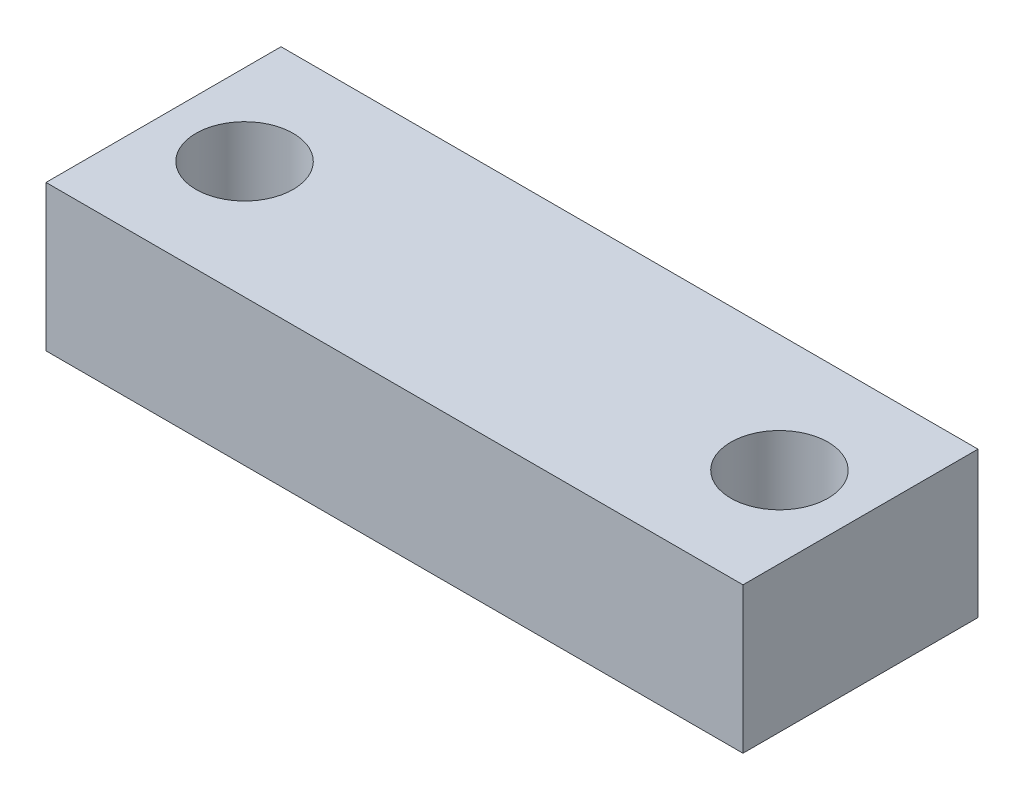
SolidWorks part; units mm, degrees
ref_plane "Front Plane" through (0, 0, 0) normal (0, 0, 1) x (1, 0, 0)
ref_plane "Top Plane" through (0, 0, 0) normal (0, 1, 0) x (1, 0, 0)
ref_plane "Right Plane" through (0, 0, 0) normal (1, 0, 0) x (0, 0, -1)
sketch "Sketch1" plane through (0, 0, 0) normal (0, 1, 0) x (1, 0, 0)
  line L1 (-21.5, 7.25) -> (21.5, 7.25)
  line L2 (-21.5, 7.25) -> (-21.5, -7.25)
  line L3 (-21.5, -7.25) -> (21.5, -7.25)
  line L4 (21.5, 7.25) -> (21.5, -7.25)
  line L5 (-21.5, 7.25) -> (21.5, -7.25) construction
  line L6 (-21.5, -7.25) -> (21.5, 7.25) construction
  point P0 (0, 0)
  dimension "D1" = 43
  dimension "D2" = 14.5
extrude "Boss-Extrude1" add sketch "Sketch1" along normal blind 9
sketch "Sketch2" plane through (0, 9, 0) normal (0, 1, 0) x (1, 0, 0)
  line L0 (-21.5, 0) -> (-16.5, 0) construction
  line L1 (-21.5, 7.25) -> (-21.5, -7.25) construction
  line L2 (0, 7.25) -> (0, -7.25) construction
  line L3 (21.5, 7.25) -> (-21.5, 7.25) construction
  line L4 (-21.5, -7.25) -> (21.5, -7.25) construction
  circle A0 centre (-16.5, 0) radius 3
  circle A1 centre (16.5, 0) radius 3
  dimension "D2" = 6
  dimension "D1" = 5
extrude "Cut-Extrude1" cut sketch "Sketch2" against normal blind 9
